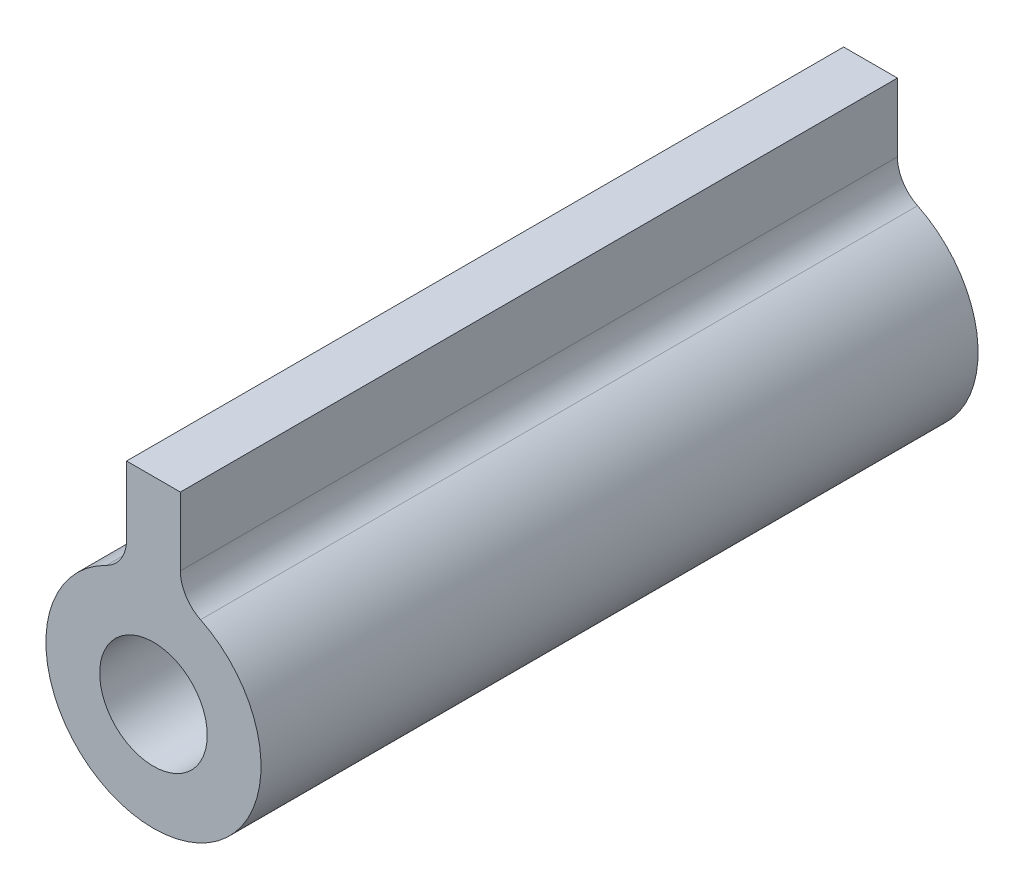
SolidWorks part; units mm, degrees
ref_plane "Front Plane" through (0, 0, 0) normal (0, 0, 1) x (1, 0, 0)
ref_plane "Top Plane" through (0, 0, 0) normal (0, 1, 0) x (1, 0, 0)
ref_plane "Right Plane" through (0, 0, 0) normal (1, 0, 0) x (0, 0, -1)
sketch "Sketch1" plane through (0, 0, 0) normal (0, 0, 1) x (1, 0, 0)
  line L0 (-1.5, 5.8095) -> (-1.5, 11)
  line L3 (-1.5, 11) -> (1.5, 11)
  line L9 (1.5, 5.8095) -> (1.5, 11)
  circle A0 centre (0, 0) radius 3
  arc A1 (-1.5, 5.8095) -> (1.5, 5.8095) centre (0, 0) ccw
  point P4 (0, 6)
  dimension "D1" = 6
  dimension "D2" = 12
  dimension "D4" = 3
extrude "Boss-Extrude1" add sketch "Sketch1" along normal blind 40
fillet "Fillet1" radius 2 2 edges at (-1.5, 5.8095, 20) (1.5, 5.8095, 20)
